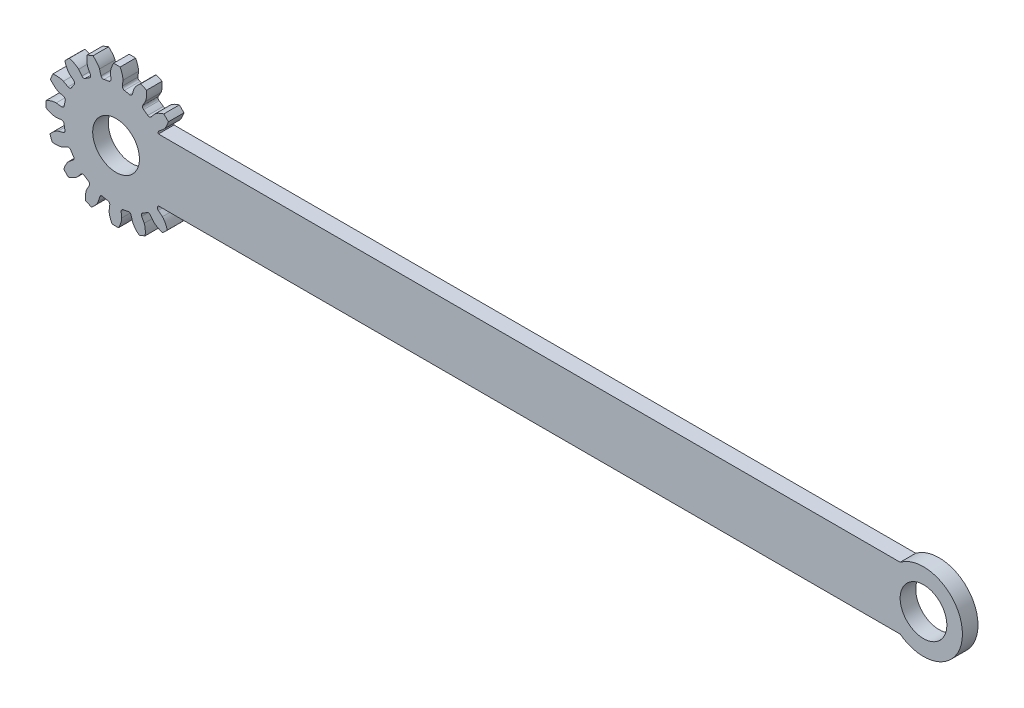
SolidWorks part; units mm, degrees
ref_plane "Front Plane" through (0, 0, 0) normal (0, 0, 1) x (1, 0, 0)
ref_plane "Top Plane" through (0, 0, 0) normal (0, 1, 0) x (1, 0, 0)
ref_plane "Right Plane" through (0, 0, 0) normal (1, 0, 0) x (0, 0, -1)
sketch "Sketch1" plane through (0, 0, 0) normal (0, 0, 1) x (1, 0, 0)
  line L1 (12.7988, -6.35) -> (159.9195, -6.35)
  line L3 (12.7988, 6.35) -> (159.9195, 6.35)
  arc A1 (159.9195, -6.35) -> (159.9195, 6.35) centre (164.682, 0) ccw
  arc A2 (12.7988, 6.35) -> (12.7988, -6.35) centre (0, 0) ccw
  dimension "D4" = 15.875
  dimension "D2" = 28.575
  dimension "D1" = 12.7
extrude "Boss-Extrude1" add sketch "Sketch1" along normal blind 3.175
sketch "Sketch3" plane through (0, 0, 3.175) normal (0, 0, 1) x (1, 0, 0)
  line L0 (0, 0) -> (10.3045, 2.9396) construction
  line L1 (10.3045, 2.9396) -> (11.8238, 3.373)
  line L2 (0, 0) -> (10.6697, 0.9912) construction
  line L3 (10.6697, 0.9912) -> (12.2428, 1.1373)
  line L4 (0, 0) -> (19.1436, 0) construction
  circle A0 centre (0, 0) radius 14.2875 construction
  circle A1 centre (0, 0) radius 12.7 construction
  circle A2 centre (0, 0) radius 12.2955 construction
  circle A3 centre (0, 0) radius 10.7156 construction
  arc A6 (10.3045, 2.9396) -> (10.6697, 0.9912) centre (0, 0) cw
  arc A7 (13.4917, 4.7018) -> (14.2787, 0.5026) centre (0, 0) cw
  spline S0 degree 4 poles (11.8238, 3.373) (11.8268, 3.3739) (11.8354, 3.3766) (11.8513, 3.3821) (11.8772, 3.3918) (11.9098, 3.4051) (11.9516, 3.4234) (12.0003, 3.4463) (12.0533, 3.473) (12.1104, 3.5037) (12.1667, 3.5357) (12.2225, 3.5689) (12.2775, 3.6031) (12.3435, 3.6459) (12.4219, 3.6992) (12.5123, 3.7642) (12.6132, 3.8411) (12.7145, 3.9229) (12.8128, 4.0062) (12.9104, 4.0936) (13.0037, 4.1803) (13.099, 4.2737) (13.186, 4.3615) (13.2815, 4.4634) (13.358, 4.5466) (13.4567, 4.6602) (13.5144, 4.7283) (13.5811, 4.8094) (13.6104, 4.846) (13.6284, 4.8686) knots 0 0 0 0 0 0.005377 0.015084 0.028532 0.04661 0.064855 0.092111 0.119476 0.146842 0.174209 0.201575 0.228941 0.256307 0.307035 0.361767 0.4165 0.471232 0.525964 0.580697 0.635429 0.690161 0.744894 0.799626 0.854358 0.909091 0.954545 1 1 1 1 1 construction
  spline S1 degree 4 poles (11.8238, 3.373) (11.8268, 3.3739) (11.8354, 3.3766) (11.8513, 3.3821) (11.8772, 3.3918) (11.9098, 3.4051) (11.9516, 3.4234) (12.0003, 3.4463) (12.0533, 3.473) (12.1104, 3.5037) (12.1667, 3.5357) (12.2225, 3.5689) (12.2775, 3.6031) (12.3435, 3.6459) (12.4219, 3.6992) (12.5123, 3.7642) (12.6132, 3.8411) (12.7145, 3.9229) (12.8128, 4.0062) (12.9104, 4.0936) (13.0037, 4.1803) (13.099, 4.2737) (13.186, 4.3615) (13.2815, 4.4634) (13.358, 4.5466) (13.4353, 4.6355) (13.4727, 4.6792) (13.4917, 4.7018) knots 0 0 0 0 0 0.005377 0.015084 0.028532 0.04661 0.064855 0.092111 0.119476 0.146842 0.174209 0.201575 0.228941 0.256307 0.307035 0.361767 0.4165 0.471232 0.525964 0.580697 0.635429 0.690161 0.744894 0.799626 0.854358 0.909091 0.909091 0.909091 0.909091 0.909091
  spline S2 degree 4 poles (12.2428, 1.1373) (12.2459, 1.1376) (12.2548, 1.1381) (12.2717, 1.1388) (12.2993, 1.1391) (12.3346, 1.1385) (12.3801, 1.1366) (12.4339, 1.1329) (12.493, 1.1271) (12.5572, 1.1192) (12.6214, 1.1098) (12.6853, 1.0991) (12.749, 1.0871) (12.8261, 1.0711) (12.9184, 1.0498) (13.0262, 1.0219) (13.1482, 0.9868) (13.2722, 0.9472) (13.3939, 0.9051) (13.5166, 0.8591) (13.635, 0.812) (13.7575, 0.7595) (13.8704, 0.7091) (13.9964, 0.6487) (14.0978, 0.5988) (14.231, 0.5288) (14.3094, 0.4861) (14.401, 0.4347) (14.4415, 0.4112) (14.4665, 0.3967) knots 0 0 0 0 0 0.005377 0.015084 0.028532 0.04661 0.064855 0.092111 0.119476 0.146842 0.174209 0.201575 0.228941 0.256307 0.307035 0.361767 0.4165 0.471232 0.525964 0.580697 0.635429 0.690161 0.744894 0.799626 0.854358 0.909091 0.954545 1 1 1 1 1 construction
  spline S3 degree 4 poles (12.2428, 1.1373) (12.2459, 1.1376) (12.2548, 1.1381) (12.2717, 1.1388) (12.2993, 1.1391) (12.3346, 1.1385) (12.3801, 1.1366) (12.4339, 1.1329) (12.493, 1.1271) (12.5572, 1.1192) (12.6214, 1.1098) (12.6853, 1.0991) (12.749, 1.0871) (12.8261, 1.0711) (12.9184, 1.0498) (13.0262, 1.0219) (13.1482, 0.9868) (13.2722, 0.9472) (13.3939, 0.9051) (13.5166, 0.8591) (13.635, 0.812) (13.7575, 0.7595) (13.8704, 0.7091) (13.9964, 0.6487) (14.0978, 0.5988) (14.2021, 0.5439) (14.2528, 0.5168) (14.2787, 0.5026) knots 0 0 0 0 0 0.005377 0.015084 0.028532 0.04661 0.064855 0.092111 0.119476 0.146842 0.174209 0.201575 0.228941 0.256307 0.307035 0.361767 0.4165 0.471232 0.525964 0.580697 0.635429 0.690161 0.744894 0.799626 0.854358 0.909091 0.909091 0.909091 0.909091 0.909091
  dimension "D1" = 28.575
  dimension "D2" = 25.4
  dimension "D3" = 24.591
  dimension "D4" = 21.4312
  dimension "D5" = 12.2955
  dimension "D6" = 14.2875
  dimension "D7" = 12.2955
  dimension "D8" = 14.2875
  dimension "D9" = 10.615
  dimension "D10" = 15.922
extrude "Cut-Extrude1" cut sketch "Sketch3" against normal through all
fillet "Fillet1" radius 0.4962 2 edges at (10.3045, 2.9396, 1.5875) (10.6697, 0.9912, 1.5875)
pattern_circular "CirPattern1" count 16 over 360 about axis through (0, 0, 3.175) along (0, 0, 1) of "Fillet1", "Cut-Extrude1"
ref_plane "Plane1" through (10.16, 0, 0) normal (1, 0, 0) x (0, 0, -1)
sketch "Sketch4" plane through (10.16, 0, 0) normal (1, 0, 0) x (0, 0, -1)
  line L6 (0, 6.35) -> (-3.175, 6.35)
  line L8 (0, 6.35) -> (0, -6.35)
  line L9 (0, -6.35) -> (-3.175, -6.35)
  line L10 (-3.175, 6.35) -> (-3.175, -6.35)
  line L11 (0, 6.35) -> (-3.175, -6.35) construction
  line L12 (0, -6.35) -> (-3.175, 6.35) construction
  point P0 (-1.5875, 0)
  dimension "D1" = 3.175
  dimension "D2" = 12.7
extrude "Boss-Extrude2" add sketch "Sketch4" against normal mid plane 10.16
sketch "Sketch5" plane through (0, 0, 3.175) normal (0, 0, 1) x (1, 0, 0)
  circle A0 centre (0, 0) radius 4.7625
  circle A1 centre (164.682, 0) radius 4.7625
  dimension "D1" = 9.525
extrude "Cut-Extrude2" cut sketch "Sketch5" against normal through all
equation "\"DiametralPitch\"= 16"
equation "\"NumTeeth\"= 16"
equation "\"PressureAngle\"= 14.5deg"
equation "\"Addendum\"= 1 / \"DiametralPitch\""
equation "\"Dedendum\"= 1.25 / \"DiametralPitch\""
equation "\"WorkingDepth\"= 2 / \"DiametralPitch\""
equation "\"WholeDepth\"= 2.25 / \"DiametralPitch\""
equation "\"Clearance\"= 0.25 / \"DiametralPitch\""
equation "\"ToothThickness\"= 1.5708 / \"DiametralPitch\""
equation "\"CircularPitch\"= pi / \"DiametralPitch\""
equation "\"PitchCircle\"= \"NumTeeth\" / \"DiametralPitch\""
equation "\"OutsideDiameter\"= ( \"NumTeeth\" + 2 ) / \"DiametralPitch\""
equation "\"Fillet\"= \"Clearance\" * cos ( \"PressureAngle\" ) * tan ( ( 90 + \"PressureAngle\" ) / 2 )"
equation "\"AddendumCircle\"= \"PitchCircle\" + ( 2 * \"Addendum\" )"
equation "\"DedendumCircle\"= \"PitchCircle\" - ( 2 * \"Dedendum\" )"
equation "\"BaseCircle\"= \"PitchCircle\" * cos ( \"PressureAngle\" )"
equation "\"PitchAngle\"= 360deg / \"NumTeeth\""
equation "\"Alpha\"= sqr ( \"PitchCircle\" ^ 2 - \"BaseCircle\" ^ 2 ) / \"BaseCircle\" * 180 / PI - \"PressureAngle\""
equation "\"Beta\"= ( \"PitchAngle\" / 4 - \"Alpha\" )"
equation "\"Phi\"= sqr ( ( \"AddendumCircle\" / 2 ) ^ 2 - ( \"BaseCircle\" / 2 ) ^ 2 ) / ( \"BaseCircle\" / 2 )"
equation "\"D2@Sketch1\"= \"OutsideDiameter\""
equation "\"D1@Sketch3\"=\"OutsideDiameter\""
equation "\"D2@Sketch3\"=\"PitchCircle\""
equation "\"D3@Sketch3\"=\"BaseCircle\""
equation "\"D4@Sketch3\"=\"DedendumCircle\""
equation "\"D1@Fillet1\"=\"Fillet\""
equation "\"D1@CirPattern1\"=\"NumTeeth\""
